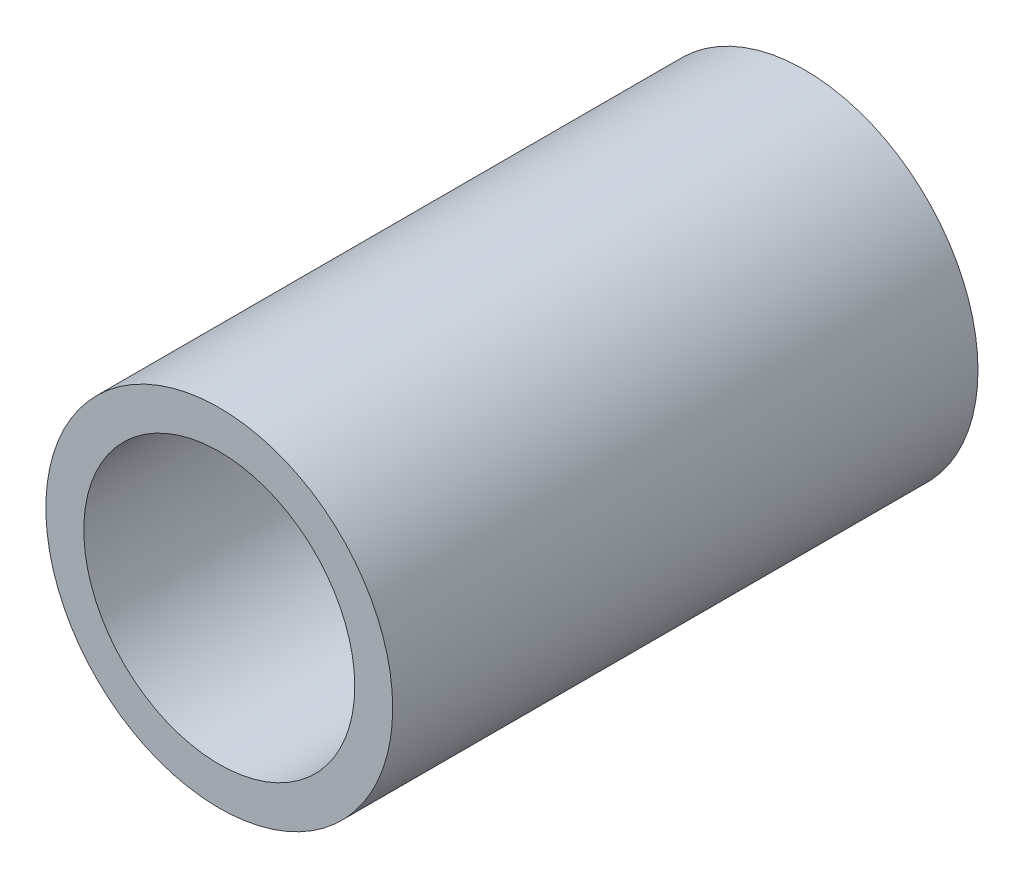
SolidWorks part; units mm, degrees
ref_plane "Front Plane" through (0, 0, 0) normal (0, 0, 1) x (1, 0, 0)
ref_plane "Top Plane" through (0, 0, 0) normal (0, 1, 0) x (1, 0, 0)
ref_plane "Right Plane" through (0, 0, 0) normal (1, 0, 0) x (0, 0, -1)
sketch "Sketch1" plane through (0, 0, 0) normal (0, 0, 1) x (1, 0, 0)
  circle A0 centre (0, 0) radius 16
  dimension "D1" = 32
extrude "Boss-Extrude3" add sketch "Sketch1" along normal blind 54
sketch "Sketch2" plane through (0, 0, 54) normal (0, 0, 1) x (1, 0, 0)
  circle A0 centre (0, 0) radius 16 construction
  circle A1 centre (0, 0) radius 16
  circle A2 centre (0, 0) radius 12.5
  dimension "D1" = 32
  dimension "D2" = 25
extrude "Cut-Extrude2" cut sketch "Sketch2" against normal blind 54 contours A2
